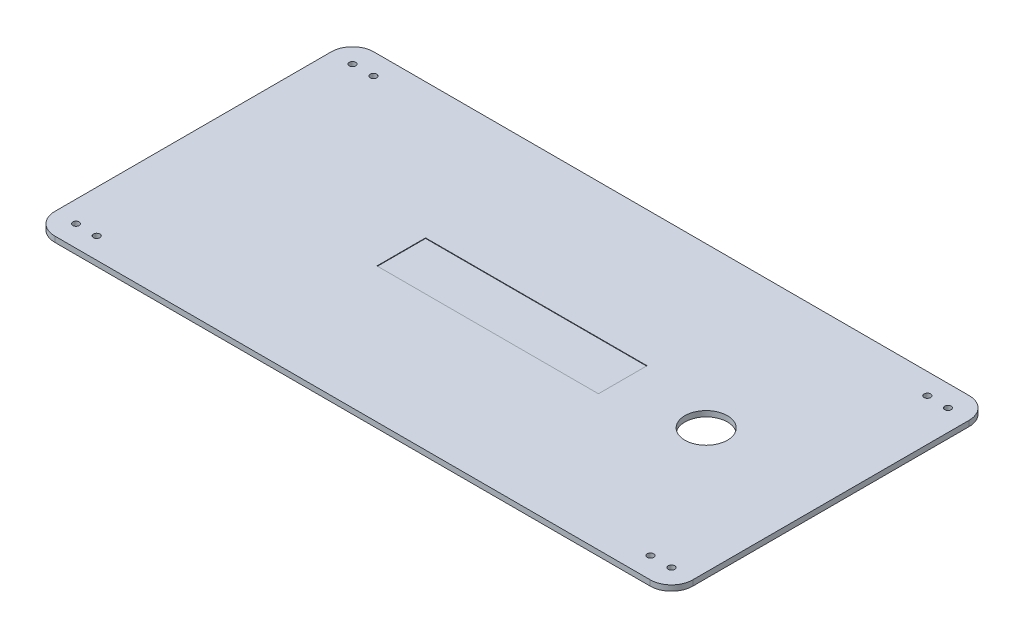
SolidWorks part; units mm, degrees
ref_plane "Front Plane" through (0, 0, 0) normal (0, 0, 1) x (1, 0, 0)
ref_plane "Top Plane" through (0, 0, 0) normal (0, 1, 0) x (1, 0, 0)
ref_plane "Right Plane" through (0, 0, 0) normal (1, 0, 0) x (0, 0, -1)
sketch "Sketch1" plane through (0, 0, 0) normal (0, 1, 0) x (1, 0, 0)
  line L1 (0, 0) -> (300, 0)
  line L2 (0, 0) -> (0, -150)
  line L3 (0, -150) -> (300, -150)
  line L4 (300, 0) -> (300, -150)
  dimension "D1" = 150
  dimension "D2" = 300
extrude "Boss-Extrude1" add sketch "Sketch1" along normal blind 2.6 contours L1 L4 L3 L2
fillet "Fillet1" radius 10 4 edges at (0, 1.3, 0) (0, 1.3, 150) (300, 1.3, 150) (300, 1.3, 0)
sketch "Sketch6" plane through (0, 0, 0) normal (0, -1, 0) x (1, 0, 0)
  line L0 (300, 10) -> (300, 140) construction
  line L1 (10, 0) -> (290, 0) construction
  circle A0 centre (290, 10) radius 1.5
  dimension "D1" = 3
  dimension "D2" = 10
  dimension "D3" = 10
ref_plane "Plane1" through (150, 0, 0) normal (1, 0, 0) x (0, 0, -1)
extrude "Cut-Extrude6" cut sketch "Sketch6" against normal blind 2.6 contours A0
ref_plane "Plane14" through (0, 0, 75) normal (0, 0, 1) x (1, 0, 0)
mirror "Mirror5" about plane through (150, 0, 0) normal (1, 0, 0) of "Cut-Extrude6"
mirror "Mirror6" about plane through (0, 0, 75) normal (0, 0, 1) of "Mirror5", "Cut-Extrude6"
sketch "Sketch15" plane through (0, 0, 0) normal (0, -1, 0) x (1, 0, 0)
  line L0 (150, 0) -> (150, 150) construction
  line L2 (0, 75) -> (300, 75) construction
  line L4 (0, 10) -> (0, 140) construction
  line L5 (300, 10) -> (300, 140) construction
  line L6 (10, 0) -> (290, 0) construction
  line L7 (10, 150) -> (290, 150) construction
  circle A0 centre (241.3, 75) radius 10
  point P14 (150, 75)
  dimension "D1" = 20
sketch "Sketch23" plane through (0, 2.6, 0) normal (0, 1, 0) x (1, 0, 0)
  circle A0 centre (19.812, -9.906) radius 1.524
extrude "Cut-Extrude16" cut sketch "Sketch23" against normal blind 2.6
mirror "Mirror7" about plane through (150, 0, 0) normal (1, 0, 0) of "Cut-Extrude16"
mirror "Mirror8" about plane through (0, 0, 75) normal (0, 0, 1) of "Mirror7", "Cut-Extrude16"
extrude "Cut-Extrude19" cut sketch "Sketch15" against normal through all contours A0
sketch "Sketch25" plane through (0, 2.6, 0) normal (0, 1, 0) x (1, 0, 0)
  line L0 (0, -75) -> (300, -75) construction
  line L1 (0, -10) -> (0, -140) construction
  line L2 (300, -10) -> (300, -140) construction
  line L3 (150, 0) -> (150, -150) construction
  line L4 (10, 0) -> (290, 0) construction
  line L5 (10, -150) -> (290, -150) construction
  line L7 (97.93, -86.43) -> (202.07, -86.43)
  line L8 (97.93, -86.43) -> (97.93, -63.57)
  line L9 (97.93, -63.57) -> (202.07, -63.57)
  line L10 (202.07, -86.43) -> (202.07, -63.57)
  line L11 (97.93, -86.43) -> (202.07, -63.57) construction
  line L12 (97.93, -63.57) -> (202.07, -86.43) construction
  point P12 (150, -75)
  dimension "D1" = 104.14
  dimension "D2" = 22.86
extrude "Cut-Extrude20" cut sketch "Sketch25" against normal blind 0.254
